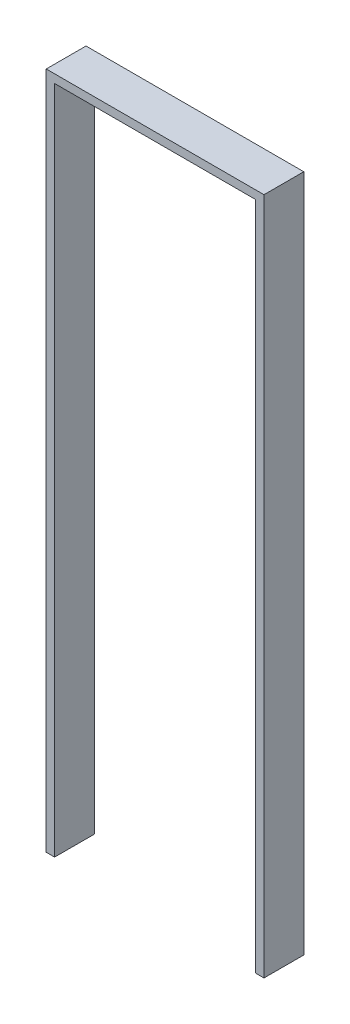
SolidWorks part; units mm, degrees
ref_plane "Front Plane" through (0, 0, 0) normal (0, 0, 1) x (1, 0, 0)
ref_plane "Top Plane" through (0, 0, 0) normal (0, 1, 0) x (1, 0, 0)
ref_plane "Right Plane" through (0, 0, 0) normal (1, 0, 0) x (0, 0, -1)
sketch "Sketch1" plane through (0, 0, 0) normal (0, 0, 1) x (1, 0, 0)
  line L0 (-304.8, 0) -> (304.8, 0) construction
  line L1 (-304.8, 0) -> (-304.8, 2032)
  line L2 (-304.8, 2032) -> (304.8, 2032)
  line L3 (304.8, 2032) -> (304.8, 0)
  line L4 (304.8, 0) -> (330.2, 0)
  line L5 (330.2, 0) -> (330.2, 2057.4)
  line L6 (330.2, 2057.4) -> (-330.2, 2057.4)
  line L7 (-330.2, 2057.4) -> (-330.2, 0)
  line L8 (-330.2, 0) -> (-304.8, 0)
  line L9 (0, 2032) -> (0, 2057.4) construction
  dimension "D1" = 25.4
  dimension "D2" = 660.4
  dimension "D3" = 2057.4
extrude "Boss-Extrude1" add sketch "Sketch1" against normal blind 120.65
